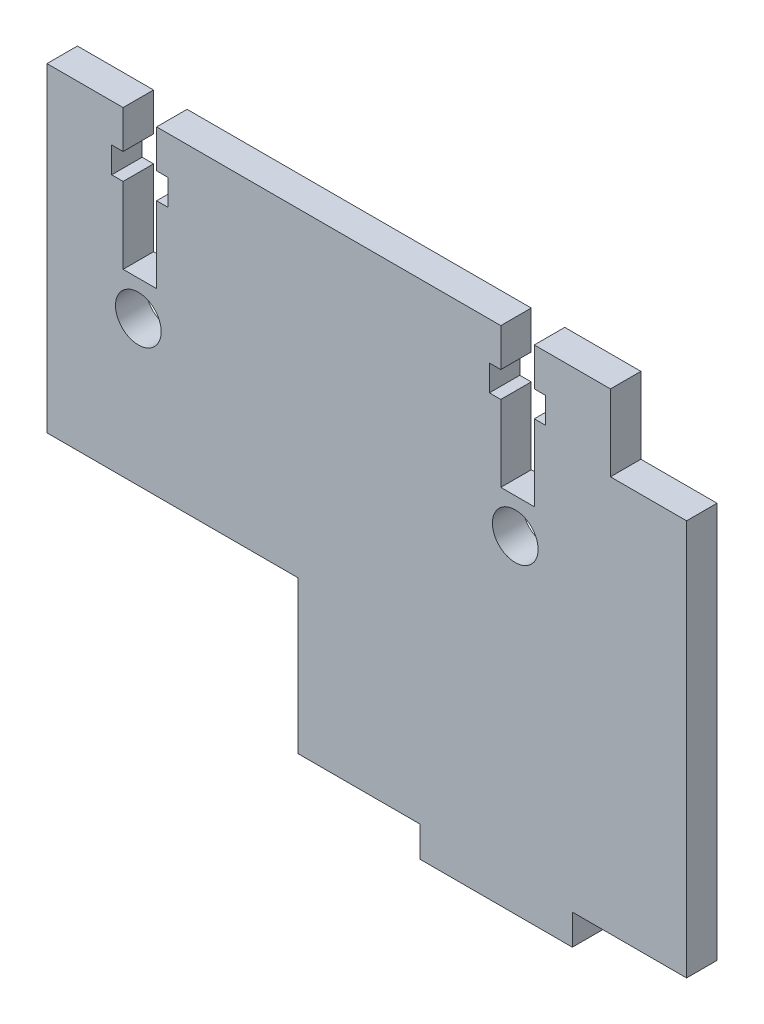
SolidWorks part; units mm, degrees
ref_plane "Front Plane" through (0, 0, 0) normal (0, 0, 1) x (1, 0, 0)
ref_plane "Top Plane" through (0, 0, 0) normal (0, 1, 0) x (1, 0, 0)
ref_plane "Right Plane" through (0, 0, 0) normal (1, 0, 0) x (0, 0, -1)
sketch "Sketch1" plane through (0, 0, 0) normal (0, 0, 1) x (1, 0, 0)
  line L0 (27, -31) -> (27, -35)
  line L1 (-42, 31) -> (42, 31)
  line L2 (-42, 31) -> (-42, -31)
  line L3 (-42, -31) -> (7, -31)
  line L4 (42, 31) -> (42, -31)
  line L5 (27, -35) -> (7, -35)
  line L6 (7, -35) -> (7, -31)
  line L7 (27, -31) -> (42, -31)
  dimension "D1" = 84
  dimension "D2" = 62
  dimension "D3" = 31
  dimension "D4" = 42
  dimension "D5" = 20
  dimension "D6" = 15
  dimension "D7" = 4
extrude "Boss-Extrude1" add sketch "Sketch1" along normal blind 4
sketch "Sketch2" plane through (0, 0, 0) normal (0, 0, -1) x (-1, 0, 0)
  line L1 (42, -31) -> (9, -31)
  line L2 (42, -31) -> (42, -11)
  line L3 (42, -11) -> (9, -11)
  line L4 (9, -31) -> (9, -11)
  line L5 (-42, 31) -> (-32, 31)
  line L6 (-42, 31) -> (-42, 21)
  line L7 (-42, 21) -> (-32, 21)
  line L8 (-32, 31) -> (-32, 21)
  dimension "D1" = 33
  dimension "D2" = 20
  dimension "D3" = 10
  dimension "D4" = 10
extrude "Cut-Extrude1" cut sketch "Sketch2" against normal blind 5
sketch "Sketch3" plane through (0, 0, 0) normal (0, 0, -1) x (-1, 0, 0)
  line L0 (29.8, 10.8) -> (29.8, 25.6452) construction
  line L1 (32, 22.6) -> (32, 12.6)
  line L2 (27.6, 26) -> (27.6, 31)
  line L3 (33.5, 26) -> (32, 26)
  line L4 (33.5, 22.6) -> (33.5, 26)
  line L5 (32, 22.6) -> (33.5, 22.6)
  line L6 (26.1, 26) -> (27.6, 26)
  line L7 (26.1, 22.6) -> (26.1, 26)
  line L8 (27.6, 22.6) -> (26.1, 22.6)
  line L9 (27.6, 12.6) -> (32, 12.6)
  line L10 (32, 31) -> (32, 26)
  line L11 (27.6, 31) -> (32, 31)
  line L12 (27.6, 12.6) -> (27.6, 22.6)
  line L13 (-32, 31) -> (42, 31) construction
  line L14 (42, 31) -> (42, -11) construction
  line L15 (-19.8, 10.8) -> (-19.8, 25.6452) construction
  line L16 (-17.6, 22.6) -> (-17.6, 12.6)
  line L17 (-22, 26) -> (-22, 31)
  line L18 (-16.1, 26) -> (-17.6, 26)
  line L19 (-16.1, 22.6) -> (-16.1, 26)
  line L20 (-17.6, 22.6) -> (-16.1, 22.6)
  line L21 (-23.5, 26) -> (-22, 26)
  line L22 (-23.5, 22.6) -> (-23.5, 26)
  line L23 (-22, 22.6) -> (-23.5, 22.6)
  line L24 (-22, 12.6) -> (-17.6, 12.6)
  line L25 (-17.6, 31) -> (-17.6, 26)
  line L26 (-22, 31) -> (-17.6, 31)
  line L27 (-22, 12.6) -> (-22, 22.6)
  line L28 (-42, -31) -> (-42, 21) construction
  dimension "D1" = 5
  dimension "D2" = 3.4
  dimension "D3" = 10
  dimension "D4" = 2.2
  dimension "D5" = 4.4
  dimension "D6" = 1.5
  dimension "D7" = 1.5
  dimension "D8" = 10
  dimension "D9" = 5
  dimension "D10" = 3.4
  dimension "D11" = 10
  dimension "D12" = 2.2
  dimension "D13" = 4.4
  dimension "D14" = 1.5
  dimension "D15" = 1.5
  dimension "D16" = 20
extrude "Cut-Extrude2" cut sketch "Sketch3" against normal blind 10
sketch "Sketch4" plane through (0, 0, 0) normal (0, 0, -1) x (-1, 0, 0)
  line L0 (-17.6, 31) -> (27.6, 31) construction
  line L1 (42, 31) -> (42, -11) construction
  circle A0 centre (30, 8) radius 3
  circle A1 centre (-19.5, 8) radius 3
  dimension "D2" = 6
  dimension "D3" = 6
  dimension "D1" = 23
  dimension "D4" = 49.5
  dimension "D5" = 12
extrude "Cut-Extrude3" cut sketch "Sketch4" against normal blind 10
